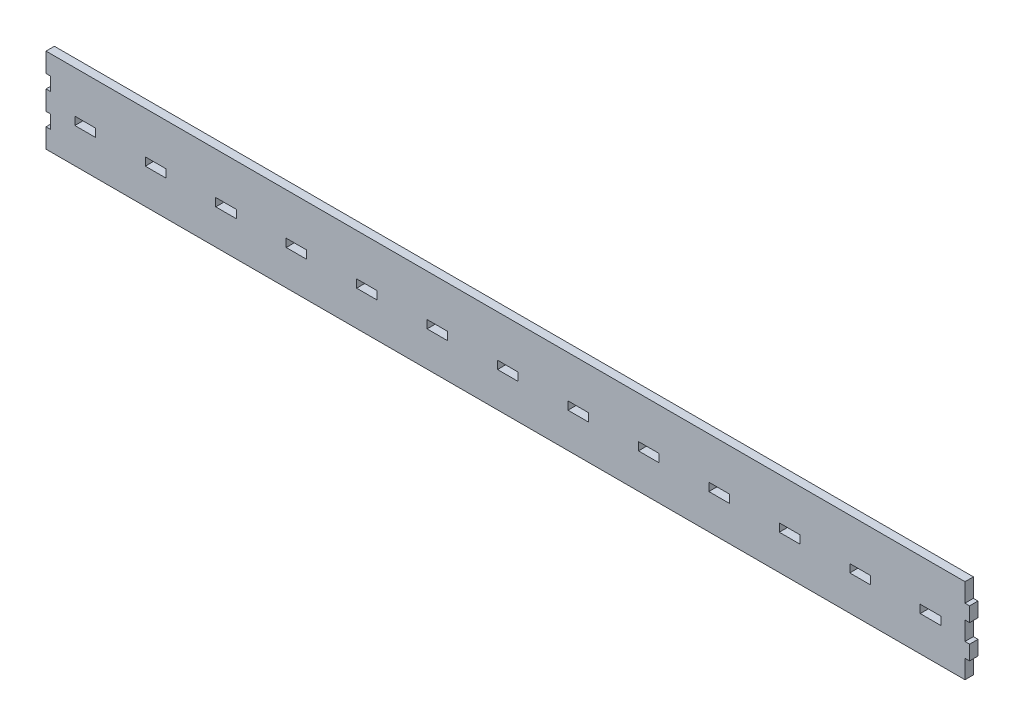
SolidWorks part; units mm, degrees
ref_plane "Спереди" through (0, 0, 0) normal (0, 0, 1) x (1, 0, 0)
ref_plane "Сверху" through (0, 0, 0) normal (0, 1, 0) x (1, 0, 0)
ref_plane "Справа" through (0, 0, 0) normal (1, 0, 0) x (0, 0, -1)
other "Configuration Table"
sketch "Эскиз1" plane through (0, 0, 0) normal (0, 0, 1) x (1, 0, 0)
  line L0 (-327.15, 0.4) -> (327.15, 0.4) construction
  line L1 (-327.15, -30.4) -> (327.15, -30.4)
  line L2 (-327.15, -16.5333) -> (-327.15, -6.9333)
  line L3 (-327.15, 30.4) -> (327.15, 30.4)
  line L4 (327.15, -30.4) -> (327.15, -17.0667)
  line L5 (-327.15, -30.4) -> (327.15, 30.4) construction
  line L6 (-327.15, 30.4) -> (327.15, -30.4) construction
  line L7 (-259.4, 0.4) -> (-259.4, -5.4)
  line L8 (-309.81, 0.4) -> (-295.11, 0.4)
  line L9 (-309.81, 0.4) -> (-309.81, -5.4)
  line L10 (-309.81, -5.4) -> (-295.11, -5.4)
  line L11 (-295.11, 0.4) -> (-295.11, -5.4)
  line L12 (-259.4, 0.4) -> (-244.7, 0.4)
  line L13 (-244.7, 0.4) -> (-244.7, -5.4)
  line L14 (-259.4, -5.4) -> (-244.7, -5.4)
  line L15 (-208.99, 0.4) -> (-208.99, -5.4)
  line L16 (-208.99, 0.4) -> (-194.29, 0.4)
  line L17 (-194.29, 0.4) -> (-194.29, -5.4)
  line L18 (-208.99, -5.4) -> (-194.29, -5.4)
  line L19 (-158.58, 0.4) -> (-158.58, -5.4)
  line L20 (-158.58, 0.4) -> (-143.88, 0.4)
  line L21 (-143.88, 0.4) -> (-143.88, -5.4)
  line L22 (-158.58, -5.4) -> (-143.88, -5.4)
  line L23 (-108.17, 0.4) -> (-108.17, -5.4)
  line L24 (-108.17, 0.4) -> (-93.47, 0.4)
  line L25 (-93.47, 0.4) -> (-93.47, -5.4)
  line L26 (-108.17, -5.4) -> (-93.47, -5.4)
  line L27 (-57.76, 0.4) -> (-57.76, -5.4)
  line L28 (-57.76, 0.4) -> (-43.06, 0.4)
  line L29 (-43.06, 0.4) -> (-43.06, -5.4)
  line L30 (-57.76, -5.4) -> (-43.06, -5.4)
  line L31 (-7.35, 0.4) -> (-7.35, -5.4)
  line L32 (-7.35, 0.4) -> (7.35, 0.4)
  line L33 (7.35, 0.4) -> (7.35, -5.4)
  line L34 (-7.35, -5.4) -> (7.35, -5.4)
  line L35 (43.06, 0.4) -> (43.06, -5.4)
  line L36 (43.06, 0.4) -> (57.76, 0.4)
  line L37 (57.76, 0.4) -> (57.76, -5.4)
  line L38 (43.06, -5.4) -> (57.76, -5.4)
  line L39 (93.47, 0.4) -> (93.47, -5.4)
  line L40 (93.47, 0.4) -> (108.17, 0.4)
  line L41 (108.17, 0.4) -> (108.17, -5.4)
  line L42 (93.47, -5.4) -> (108.17, -5.4)
  line L43 (143.88, 0.4) -> (143.88, -5.4)
  line L44 (143.88, 0.4) -> (158.58, 0.4)
  line L45 (158.58, 0.4) -> (158.58, -5.4)
  line L46 (143.88, -5.4) -> (158.58, -5.4)
  line L47 (194.29, 0.4) -> (194.29, -5.4)
  line L48 (194.29, 0.4) -> (208.99, 0.4)
  line L49 (208.99, 0.4) -> (208.99, -5.4)
  line L50 (194.29, -5.4) -> (208.99, -5.4)
  line L51 (244.7, 0.4) -> (244.7, -5.4)
  line L52 (244.7, 0.4) -> (259.4, 0.4)
  line L53 (259.4, 0.4) -> (259.4, -5.4)
  line L54 (244.7, -5.4) -> (259.4, -5.4)
  line L55 (295.11, 0.4) -> (295.11, -5.4)
  line L56 (295.11, 0.4) -> (309.81, 0.4)
  line L57 (309.81, 0.4) -> (309.81, -5.4)
  line L58 (295.11, -5.4) -> (309.81, -5.4)
  line L60 (-327.15, 30.4) -> (-330.4586, 30.4)
  line L62 (-327.15, 16.5333) -> (-330.4586, 16.5333)
  line L63 (-330.4586, 30.4) -> (-330.4586, 16.5333)
  line L64 (-327.15, 6.9333) -> (-330.4586, 6.9333)
  line L65 (-330.4586, 6.9333) -> (-330.4586, -6.9333)
  line L66 (-327.15, -6.9333) -> (-330.4586, -6.9333)
  line L68 (-327.15, -16.5333) -> (-330.4586, -16.5333)
  line L69 (-330.4586, -16.5333) -> (-330.4586, -30.4)
  line L70 (-327.15, -30.4) -> (-330.4586, -30.4)
  line L72 (327.15, 17.0667) -> (330.4586, 17.0667)
  line L74 (327.15, 6.6667) -> (330.4586, 6.6667)
  line L75 (330.4586, 17.0667) -> (330.4586, 6.6667)
  line L76 (327.15, -6.6667) -> (330.4586, -6.6667)
  line L77 (330.4586, -6.6667) -> (330.4586, -17.0667)
  line L78 (327.15, -17.0667) -> (330.4586, -17.0667)
  line L79 (-327.15, 6.9333) -> (-327.15, 16.5333)
  line L80 (327.15, 17.0667) -> (327.15, 30.4)
  line L81 (327.15, -6.6667) -> (327.15, 6.6667)
  line L82 (-327.15, -6.9333) -> (-309.81, -6.9333) construction
  line L83 (327.15, -6.6667) -> (327.15, -17.0667) construction
  line L85 (309.81, -5.4) -> (327.15, -5.4) construction
  point P0 (0, 0)
  dimension "D3" = 30
  dimension "D4" = 5.8
  dimension "D6" = 14.7
  dimension "D9" = 3.3086
  dimension "D11" = 9.6
  dimension "D12" = 10.4
  dimension "D13" = 3.3086
  dimension "D34" = 50.41
  dimension "D35" = 25
  dimension "D2" = 654.3
  dimension "D7" = 13
  dimension "D10" = 3
  dimension "D14" = 2
extrude "Бобышка-Вытянуть1" add sketch "Эскиз1" along normal blind 6
equation "\"height\"= 50"
equation "\"width\"=654.3"
equation "\"holes_offset\"= 30"
equation "\"D3@Эскиз1\"=\"holes_offset\""
equation "\"hole_height\"= 5.8"
equation "\"D4@Эскиз1\"=\"hole_height\""
equation "\"hole_offset\"=7.81804"
equation "\"hole_width\"=14.7"
equation "\"D6@Эскиз1\"=\"hole_width\""
equation "\"fanera\"=6"
equation "\"D1@Бобышка-Вытянуть1\"=\"fanera\""
equation "\"out_ship_height\"=3.30862"
equation "\"D9@Эскиз1\"=\"out_ship_height\""
equation "\"out_ship_width\"= 9.6"
equation "\"D11@Эскиз1\"=\"out_ship_width\""
equation "\"cnt\"=5"
equation "\"D10@Эскиз1\"=(\"cnt\"+1)/2"
equation "\"in_ship_width\"=10.4"
equation "\"D12@Эскиз1\"=\"in_ship_width\""
equation "\"D13@Эскиз1\"=\"out_ship_height\""
equation "\"D14@Эскиз1\"=(\"cnt\"-1)/2"
equation "\"D2@Эскиз1\"=\"width\""
